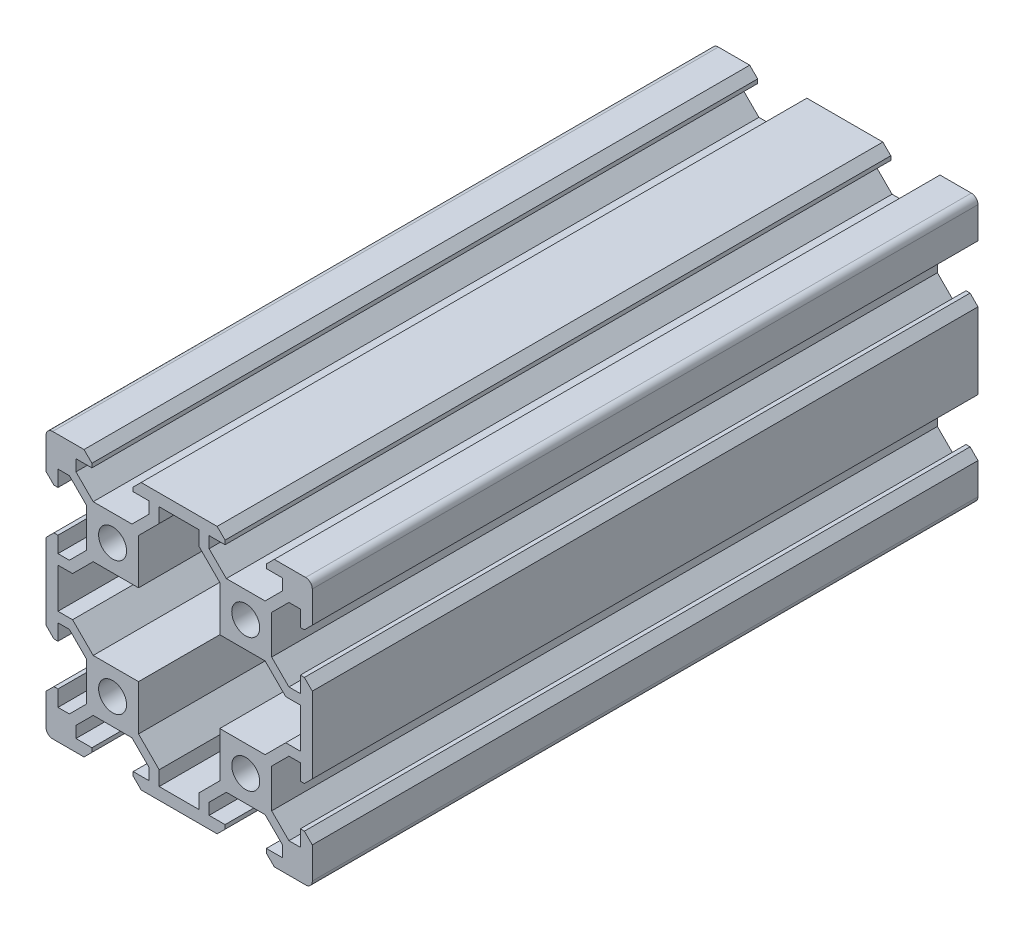
SolidWorks part; units mm, degrees
ref_plane "Front" through (0, 0, 0) normal (0, 0, 1) x (1, 0, 0)
ref_plane "Top" through (0, 0, 0) normal (0, 1, 0) x (1, 0, 0)
ref_plane "Right" through (0, 0, 0) normal (1, 0, 0) x (0, 0, -1)
sketch "草图1" plane through (0, 0, 0) normal (0, 0, 1) x (1, 0, 0)
  line L0 (0, 20) -> (0, -20) construction
  line L1 (-20, -20) -> (20, -20) construction
  line L2 (-20, -20) -> (-20, 20) construction
  line L3 (-20, 20) -> (20, 20) construction
  line L4 (20, -20) -> (20, 20) construction
  line L5 (-20, -20) -> (20, 20) construction
  line L6 (-20, 20) -> (-10, 10) construction
  line L7 (-20, 0) -> (20, 0) construction
  line L8 (5.71, 20) -> (-5.71, 20)
  line L9 (-5.71, 20) -> (-6.9, 18.81)
  line L10 (-6.9, 18.81) -> (-6.9, 18.2)
  line L11 (-6.9, 18.2) -> (-4.5, 18.2)
  line L12 (-4.5, 18.2) -> (-4.5, 16.4899)
  line L13 (-4.5, 16.4899) -> (-7.0899, 13.9)
  line L14 (-7.0899, 13.9) -> (-12.9101, 13.9)
  line L15 (-6.1, 6.1) -> (-6.1, 12.9101)
  line L16 (-6.1, 12.9101) -> (-3, 16.0101)
  line L17 (-3, 16.0101) -> (-3, 18.2)
  line L18 (-3, 18.2) -> (3, 18.2)
  line L19 (-20, 20) -> (-14.29, 20)
  line L20 (-14.29, 20) -> (-13.1, 18.81)
  line L21 (-13.1, 18.81) -> (-13.1, 18.2)
  line L22 (-13.1, 18.2) -> (-15.5, 18.2)
  line L23 (-15.5, 18.2) -> (-15.5, 16.4899)
  line L24 (-15.5, 16.4899) -> (-12.9101, 13.9)
  line L25 (-10, 10) -> (0, 20) construction
  line L26 (-10, 10) -> (-10, 20) construction
  line L27 (-13.9, 6.1) -> (-6.1, 6.1) construction
  line L28 (-13.9, 6.1) -> (-13.9, 13.9) construction
  line L29 (-13.9, 13.9) -> (-6.1, 13.9) construction
  line L30 (-6.1, 6.1) -> (-6.1, 13.9) construction
  line L31 (-13.9, 6.1) -> (-6.1, 13.9) construction
  line L32 (-13.9, 13.9) -> (-10, 10) construction
  line L35 (-10, 10) -> (-6.1, 6.1) construction
  line L37 (-10, 10) -> (20, -20) construction
  line L38 (-16.0101, -3) -> (-18.2, -3)
  line L39 (-20, 20) -> (-20, 14.29)
  line L40 (-20, 14.29) -> (-18.81, 13.1)
  line L41 (-18.81, 13.1) -> (-18.2, 13.1)
  line L42 (-18.2, 13.1) -> (-18.2, 15.5)
  line L43 (-18.2, 15.5) -> (-16.4899, 15.5)
  line L44 (-16.4899, 15.5) -> (-13.9, 12.9101)
  line L45 (-13.9, 7.0899) -> (-13.9, 12.9101)
  line L46 (-16.4899, 4.5) -> (-13.9, 7.0899)
  line L47 (-18.2, 4.5) -> (-16.4899, 4.5)
  line L48 (-18.2, 6.9) -> (-18.2, 4.5)
  line L49 (-18.81, 6.9) -> (-18.2, 6.9)
  line L50 (-20, 5.71) -> (-18.81, 6.9)
  line L51 (-20, -5.71) -> (-20, 5.71)
  line L53 (-18.2, 3) -> (-18.2, -3)
  line L54 (-16.0101, 3) -> (-18.2, 3)
  line L55 (-12.9101, 6.1) -> (-16.0101, 3)
  line L56 (-6.1, 6.1) -> (-12.9101, 6.1)
  line L57 (-12.9101, -6.1) -> (-16.0101, -3)
  line L58 (-6.1, -6.1) -> (-12.9101, -6.1)
  line L59 (-6.1, -6.1) -> (-6.1, -12.9101)
  line L60 (-6.1, -12.9101) -> (-3, -16.0101)
  line L61 (-3, -16.0101) -> (-3, -18.2)
  line L62 (-3, -18.2) -> (3, -18.2)
  line L64 (5.71, -20) -> (-5.71, -20)
  line L65 (-5.71, -20) -> (-6.9, -18.81)
  line L66 (-6.9, -18.81) -> (-6.9, -18.2)
  line L67 (-6.9, -18.2) -> (-4.5, -18.2)
  line L68 (-4.5, -18.2) -> (-4.5, -16.4899)
  line L69 (-4.5, -16.4899) -> (-7.0899, -13.9)
  line L70 (-7.0899, -13.9) -> (-12.9101, -13.9)
  line L71 (-15.5, -16.4899) -> (-12.9101, -13.9)
  line L72 (-15.5, -18.2) -> (-15.5, -16.4899)
  line L73 (-13.1, -18.2) -> (-15.5, -18.2)
  line L74 (-13.1, -18.81) -> (-13.1, -18.2)
  line L75 (-14.29, -20) -> (-13.1, -18.81)
  line L76 (-20, -20) -> (-14.29, -20)
  line L77 (-20, -20) -> (-20, -14.29)
  line L78 (-20, -14.29) -> (-18.81, -13.1)
  line L79 (-18.81, -13.1) -> (-18.2, -13.1)
  line L80 (-18.2, -13.1) -> (-18.2, -15.5)
  line L81 (-18.2, -15.5) -> (-16.4899, -15.5)
  line L82 (-16.4899, -15.5) -> (-13.9, -12.9101)
  line L83 (-13.9, -7.0899) -> (-13.9, -12.9101)
  line L84 (-16.4899, -4.5) -> (-13.9, -7.0899)
  line L85 (-18.2, -4.5) -> (-16.4899, -4.5)
  line L86 (-18.2, -6.9) -> (-18.2, -4.5)
  line L87 (-18.81, -6.9) -> (-18.2, -6.9)
  line L88 (-20, -5.71) -> (-18.81, -6.9)
  line L89 (13.9, 13.9) -> (10, 10) construction
  line L90 (13.9, 6.1) -> (6.1, 13.9) construction
  line L91 (6.1, 6.1) -> (6.1, 13.9) construction
  line L92 (13.9, 13.9) -> (6.1, 13.9) construction
  line L93 (13.9, 6.1) -> (13.9, 13.9) construction
  line L94 (13.9, 6.1) -> (6.1, 6.1) construction
  line L95 (10, 10) -> (10, 20) construction
  line L96 (10, 10) -> (0, 20) construction
  line L97 (20, -5.71) -> (18.81, -6.9)
  line L98 (18.81, -6.9) -> (18.2, -6.9)
  line L99 (18.2, -6.9) -> (18.2, -4.5)
  line L100 (18.2, -4.5) -> (16.4899, -4.5)
  line L101 (16.4899, -4.5) -> (13.9, -7.0899)
  line L102 (13.9, -7.0899) -> (13.9, -12.9101)
  line L103 (16.4899, -15.5) -> (13.9, -12.9101)
  line L104 (18.2, -15.5) -> (16.4899, -15.5)
  line L105 (18.2, -13.1) -> (18.2, -15.5)
  line L106 (18.81, -13.1) -> (18.2, -13.1)
  line L107 (20, -14.29) -> (18.81, -13.1)
  line L108 (20, -20) -> (20, -14.29)
  line L109 (20, -20) -> (14.29, -20)
  line L110 (14.29, -20) -> (13.1, -18.81)
  line L111 (13.1, -18.81) -> (13.1, -18.2)
  line L112 (13.1, -18.2) -> (15.5, -18.2)
  line L113 (15.5, -18.2) -> (15.5, -16.4899)
  line L114 (15.5, -16.4899) -> (12.9101, -13.9)
  line L115 (7.0899, -13.9) -> (12.9101, -13.9)
  line L116 (4.5, -16.4899) -> (7.0899, -13.9)
  line L117 (4.5, -18.2) -> (4.5, -16.4899)
  line L118 (6.9, -18.2) -> (4.5, -18.2)
  line L119 (6.9, -18.81) -> (6.9, -18.2)
  line L120 (5.71, -20) -> (6.9, -18.81)
  line L121 (3, -16.0101) -> (3, -18.2)
  line L122 (6.1, -12.9101) -> (3, -16.0101)
  line L123 (6.1, -6.1) -> (6.1, -12.9101)
  line L124 (6.1, -6.1) -> (12.9101, -6.1)
  line L125 (12.9101, -6.1) -> (16.0101, -3)
  line L126 (6.1, 6.1) -> (12.9101, 6.1)
  line L127 (12.9101, 6.1) -> (16.0101, 3)
  line L128 (16.0101, 3) -> (18.2, 3)
  line L129 (18.2, 3) -> (18.2, -3)
  line L130 (20, -5.71) -> (20, 5.71)
  line L131 (20, 5.71) -> (18.81, 6.9)
  line L132 (18.81, 6.9) -> (18.2, 6.9)
  line L133 (18.2, 6.9) -> (18.2, 4.5)
  line L134 (18.2, 4.5) -> (16.4899, 4.5)
  line L135 (16.4899, 4.5) -> (13.9, 7.0899)
  line L136 (13.9, 7.0899) -> (13.9, 12.9101)
  line L137 (16.4899, 15.5) -> (13.9, 12.9101)
  line L138 (18.2, 15.5) -> (16.4899, 15.5)
  line L139 (18.2, 13.1) -> (18.2, 15.5)
  line L140 (18.81, 13.1) -> (18.2, 13.1)
  line L141 (20, 14.29) -> (18.81, 13.1)
  line L142 (20, 20) -> (20, 14.29)
  line L143 (16.0101, -3) -> (18.2, -3)
  line L144 (15.5, 16.4899) -> (12.9101, 13.9)
  line L145 (15.5, 18.2) -> (15.5, 16.4899)
  line L146 (13.1, 18.2) -> (15.5, 18.2)
  line L147 (13.1, 18.81) -> (13.1, 18.2)
  line L148 (14.29, 20) -> (13.1, 18.81)
  line L149 (20, 20) -> (14.29, 20)
  line L150 (3, 16.0101) -> (3, 18.2)
  line L151 (6.1, 12.9101) -> (3, 16.0101)
  line L152 (6.1, 6.1) -> (6.1, 12.9101)
  line L153 (7.0899, 13.9) -> (12.9101, 13.9)
  line L154 (4.5, 16.4899) -> (7.0899, 13.9)
  line L155 (4.5, 18.2) -> (4.5, 16.4899)
  line L156 (6.9, 18.2) -> (4.5, 18.2)
  line L157 (6.9, 18.81) -> (6.9, 18.2)
  line L158 (5.71, 20) -> (6.9, 18.81)
  circle A0 centre (-10, 10) radius 2.1
  circle A1 centre (-10, -10) radius 2.1
  circle A2 centre (10, -10) radius 2.1
  circle A3 centre (10, 10) radius 2.1
  point P0 (0, 0)
  point P59 (-18.2, 0)
  point P124 (0, -18.2)
  point P152 (0, 18.2)
  dimension "D10" = 4.2
  dimension "D1" = 40
  dimension "D2" = 6
  dimension "D3" = 1.8
  dimension "D4" = 45
  dimension "D5" = 4.5
  dimension "D6" = 45
  dimension "D7" = 6.2
  dimension "D8" = 0.61
  dimension "D9" = 1.4
  dimension "D12" = 7.8
  dimension "D13" = 1.5
  dimension "D14" = 1.4
  dimension "D15" = 7.8
extrude "凸台-拉伸1" add sketch "草图1" along normal blind 100
ref_plane "Ebene1" through (0, 0, 0) normal (-0.7071, -0.7071, 0) x (-0.7071, 0.7071, 0)
fillet "Verrundung1" radius 1 4 edges at (20, -20, 50) (-20, -20, 50) (-20, 20, 50) (20, 20, 50)
